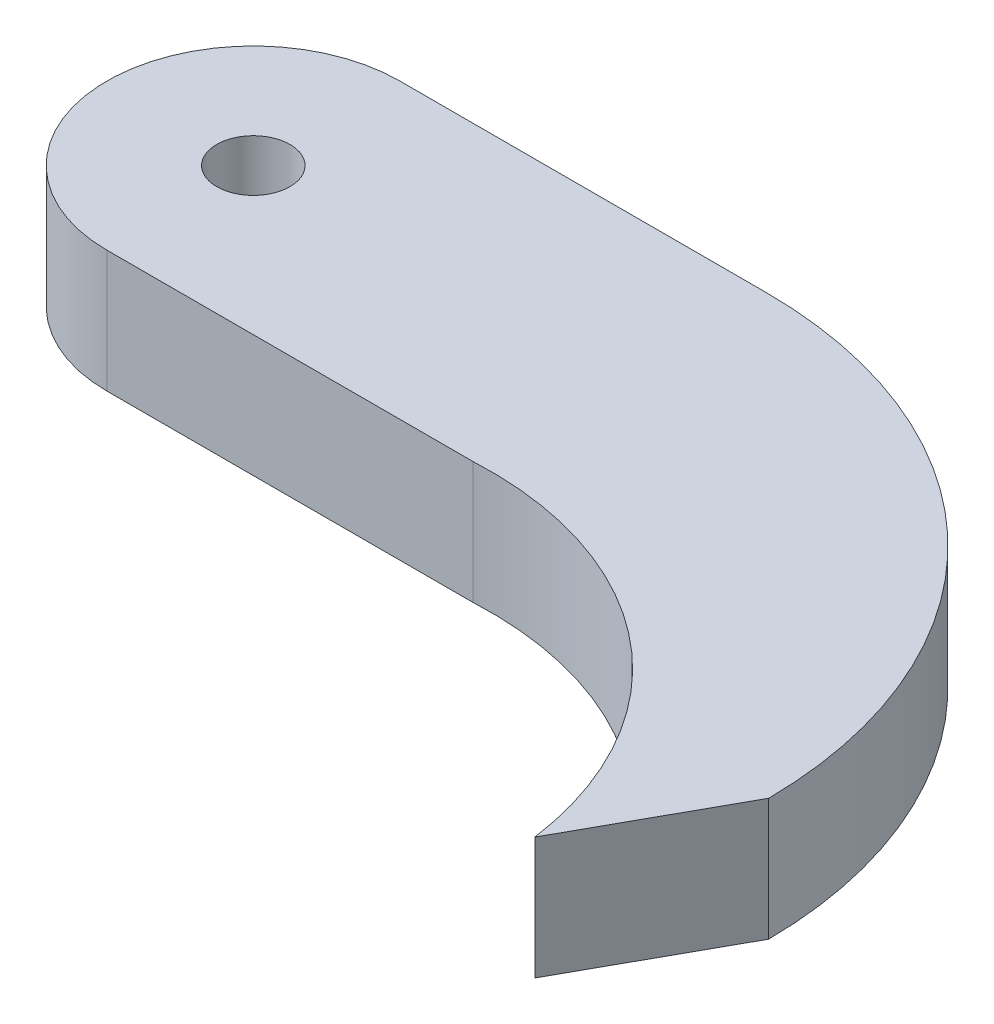
SolidWorks part; units mm, degrees
ref_plane "Front Plane" through (0, 0, 0) normal (0, 0, 1) x (1, 0, 0)
ref_plane "Top Plane" through (0, 0, 0) normal (0, 1, 0) x (1, 0, 0)
ref_plane "Right Plane" through (0, 0, 0) normal (1, 0, 0) x (0, 0, -1)
sketch "Sketch1" plane through (0, 0, 0) normal (0, 1, 0) x (1, 0, 0)
  line L0 (0, 6) -> (15, 6)
  line L1 (-29.1315, 0) -> (65.0446, 0) construction
  line L2 (32.9997, -11.8907) -> (29.5874, -18.0559)
  line L3 (0, -6) -> (15, -6)
  arc A0 (0, 6) -> (0, -6) centre (0, 0) ccw
  arc A1 (15, 6) -> (32.9997, -11.8907) centre (15, -12) cw
  arc A2 (15, -6) -> (29.5874, -18.0559) centre (15.7205, -19.9814) cw
  circle A3 centre (0, 0) radius 1.5
  dimension "D1" = 12
  dimension "D2" = 3
  dimension "D4" = 15
  dimension "D5" = 14
  dimension "D6" = 18
  dimension "D3" = 15
extrude "Boss-Extrude1" add sketch "Sketch1" along normal blind 5
